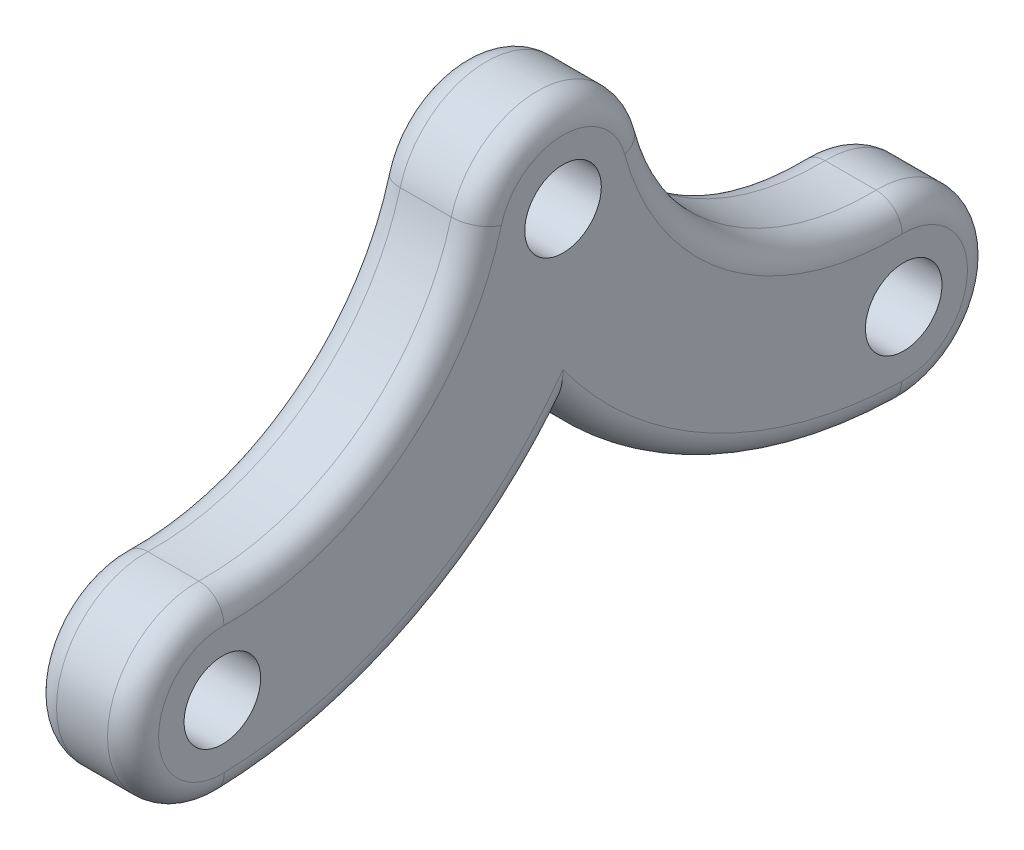
SolidWorks part; units mm, degrees
material "Alloy Steel"
ref_plane "Спереди" through (0, 0, 0) normal (0, 0, 1) x (1, 0, 0)
ref_plane "Сверху" through (0, 0, 0) normal (0, 1, 0) x (1, 0, 0)
ref_plane "Справа" through (0, 0, 0) normal (1, 0, 0) x (0, 0, -1)
sketch "Sketch1" plane through (0, 0, 0) normal (1, 0, 0) x (0, 0, -1)
  line L0 (0, 77.0459) -> (0, -15) construction
  line L1 (0, -70.7985) -> (0, -152.6446) construction
  circle A0 centre (0, 0) radius 15
  arc A1 (33.8058, 9.0648) -> (-33.8058, 9.0648) centre (0, 0) ccw
  circle A2 centre (-133.5, -100) radius 15
  arc A3 (-132.6946, -65.0093) -> (-132.4471, -134.9842) centre (-133.5, -100) ccw
  arc A4 (-33.8058, 9.0648) -> (-132.6946, -65.0093) centre (-130.3936, 34.9643) cw
  arc A6 (-132.4471, -134.9842) -> (0, -70.7985) centre (-137.8619, 44.9344) ccw
  arc A7 (132.4471, -134.9842) -> (0, -70.7985) centre (137.8619, 44.9344) cw
  arc A8 (33.8058, 9.0648) -> (132.6946, -65.0093) centre (130.3936, 34.9643) ccw
  arc A9 (132.6946, -65.0093) -> (132.4471, -134.9842) centre (133.5, -100) cw
  circle A10 centre (133.5, -100) radius 15
  arc A11 (-33.8058, 9.0648) -> (33.8058, 9.0648) centre (0, 0) cw
  dimension "D1" = 30
  dimension "D4" = 30
  dimension "D7" = 180
  dimension "D8" = 100
  dimension "D2" = 20
  dimension "D3" = 20
  dimension "D5" = 100
  dimension "D6" = 133.5
extrude "Boss-Extrude1" add sketch "Sketch1" along normal blind 40 contours A9 A8 A1 A4 A3 A6 A7 A0 A2 A10
fillet "Fillet1" radius 10 14 edges at (0, -117.0471, 59.3635) (0, -100.1238, 168.4998) (0, -45.0717, 70.4416) (0, 35, 0) (0, -117.0471, -59.3635) (0, -100.1238, -168.4998) (40, -117.0471, 59.3635) (40, -100.1238, 168.4998) (40, -45.0717, 70.4416) (40, 35, 0) (40, -117.0471, -59.3635) (40, -100.1238, -168.4998) (0, -45.0717, -70.4416) (40, -45.0717, -70.4416)
equation "\"D3@Sketch1\"=\"D2@Sketch1\""
equation "\"D4@Sketch1\"=\"D1@Sketch1\""
